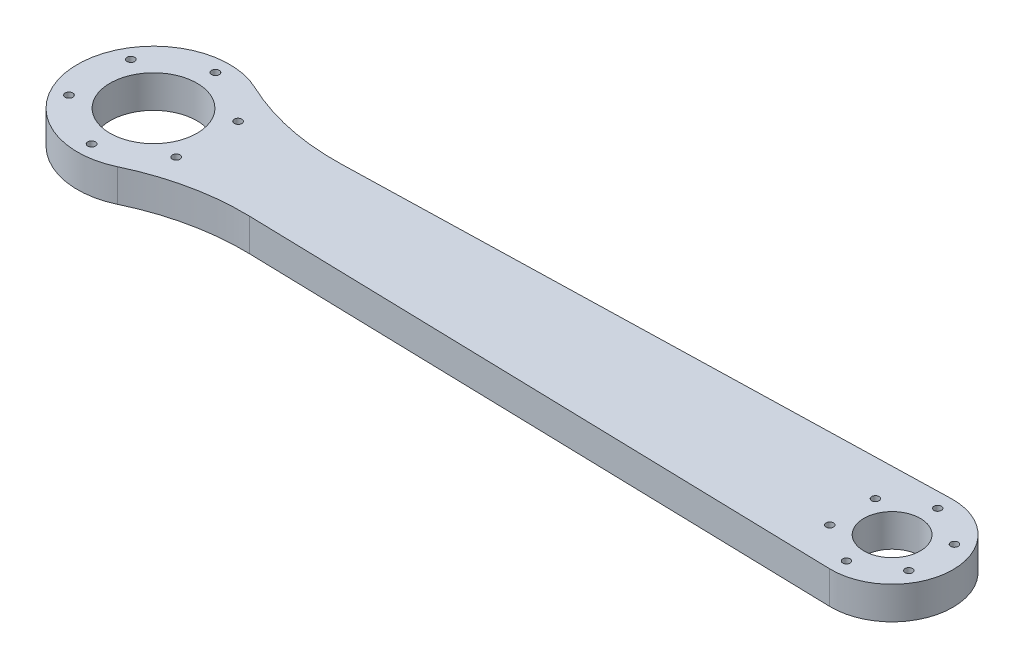
SolidWorks part; units mm, degrees
ref_plane "前视基准面" through (0, 0, 0) normal (0, 0, 1) x (1, 0, 0)
ref_plane "上视基准面" through (0, 0, 0) normal (0, 1, 0) x (1, 0, 0)
ref_plane "右视基准面" through (0, 0, 0) normal (1, 0, 0) x (0, 0, -1)
sketch "草图1" plane through (0, 0, 0) normal (0, 1, 0) x (1, 0, 0)
  line L0 (0, 0) -> (167.3119, 0) construction
  line L1 (65.1964, 20.9385) -> (339.2798, 27.9907)
  line L2 (65.1964, -20.9385) -> (339.2798, -27.9907)
  line L4 (358.1865, -10.5) -> (358.1865, 10.5) construction
  line L5 (358.1865, 10.5) -> (340, 21) construction
  line L6 (340, 21) -> (321.8135, 10.5) construction
  line L7 (321.8135, 10.5) -> (321.8135, -10.5) construction
  line L8 (321.8135, -10.5) -> (340, -21) construction
  line L9 (340, -21) -> (358.1865, -10.5) construction
  line L10 (0, 28.5) -> (-24.6817, 14.25) construction
  line L11 (-24.6817, 14.25) -> (-24.6817, -14.25) construction
  line L12 (-24.6817, -14.25) -> (0, -28.5) construction
  line L13 (0, -28.5) -> (24.6817, -14.25) construction
  line L14 (24.6817, -14.25) -> (24.6817, 14.25) construction
  line L15 (24.6817, 14.25) -> (0, 28.5) construction
  circle A0 centre (0, 0) radius 20
  circle A1 centre (0, 0) radius 35 construction
  arc A3 (15.0541, 31.5971) -> (15.0541, -31.5971) centre (0, 0) ccw
  circle A4 centre (340, 0) radius 13
  circle A5 centre (340, 0) radius 28 construction
  arc A6 (339.2798, 27.9907) -> (339.2798, -27.9907) centre (340, 0) cw
  arc A7 (15.0541, 31.5971) -> (65.1964, 20.9385) centre (62.367, 130.9021) ccw
  arc A8 (15.0541, -31.5971) -> (65.1964, -20.9385) centre (62.367, -130.9021) cw
  circle A9 centre (340, 0) radius 21 construction
  circle A10 centre (340, 0) radius 18.1865 construction
  circle A11 centre (340, 21) radius 1.7
  circle A12 centre (358.1865, 10.5) radius 1.7
  circle A13 centre (358.1865, -10.5) radius 1.7
  circle A14 centre (340, -21) radius 1.7
  circle A15 centre (321.8135, -10.5) radius 1.7
  circle A16 centre (321.8135, 10.5) radius 1.7
  circle A17 centre (0, 0) radius 28.5 construction
  circle A18 centre (0, 0) radius 24.6817 construction
  circle A19 centre (0, 28.5) radius 1.75
  circle A20 centre (-24.6817, 14.25) radius 1.75
  circle A21 centre (-24.6817, -14.25) radius 1.75
  circle A22 centre (0, -28.5) radius 1.75
  circle A23 centre (24.6817, -14.25) radius 1.75
  circle A24 centre (24.6817, 14.25) radius 1.75
  point P4 (28.7228, 20)
  point P19 (28.7228, 20)
  dimension "D1" = 40
  dimension "D3" = 70
  dimension "D4" = 26
  dimension "D6" = 56
  dimension "D7" = 110
  dimension "D8" = 42
  dimension "D9" = 3.4
  dimension "D10" = 57
  dimension "D11" = 3.5
  dimension "D2" = 20
  dimension "D5" = 340
extrude "凸台-拉伸1" add sketch "草图1" along normal blind 15
